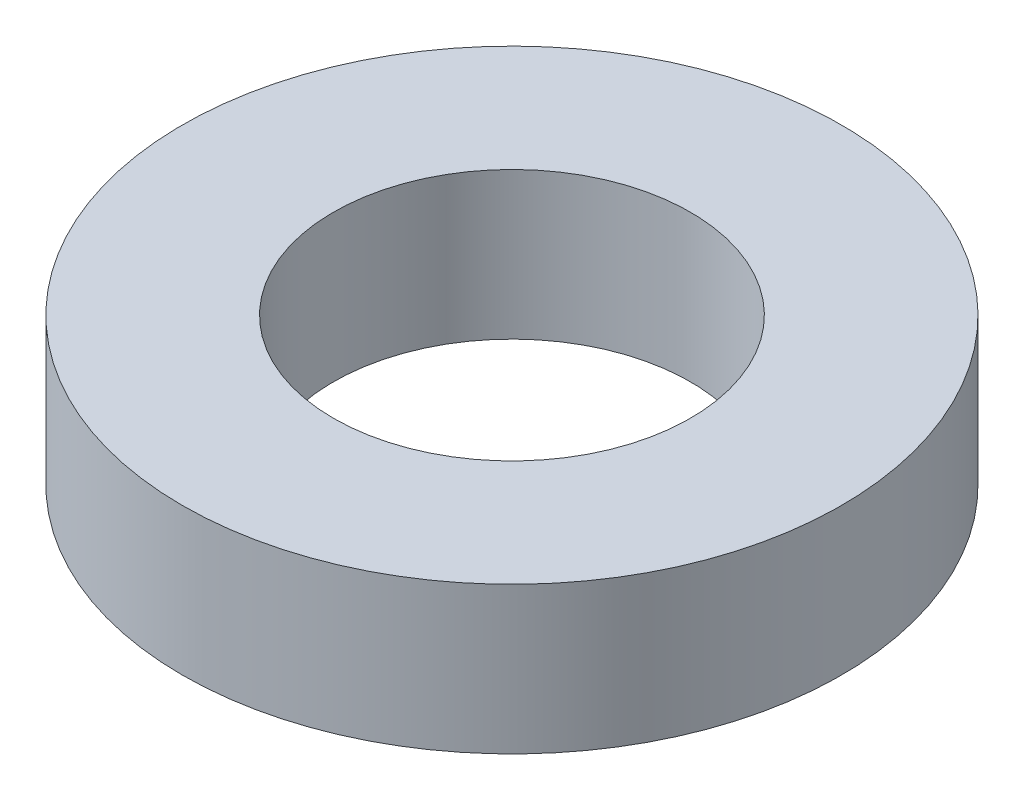
SolidWorks part; units mm, degrees
ref_plane "Front Plane" through (0, 0, 0) normal (0, 0, 1) x (1, 0, 0)
ref_plane "Top Plane" through (0, 0, 0) normal (0, 1, 0) x (1, 0, 0)
ref_plane "Right Plane" through (0, 0, 0) normal (1, 0, 0) x (0, 0, -1)
sketch "Sketch1" plane through (0, 0, 0) normal (0, 1, 0) x (1, 0, 0)
  circle A0 centre (0, 0) radius 6
  circle A1 centre (0, 0) radius 3.25
  dimension "D1" = 6.5
  dimension "D2" = 12
extrude "Boss-Extrude1" add sketch "Sketch1" along normal mid plane 2.675
